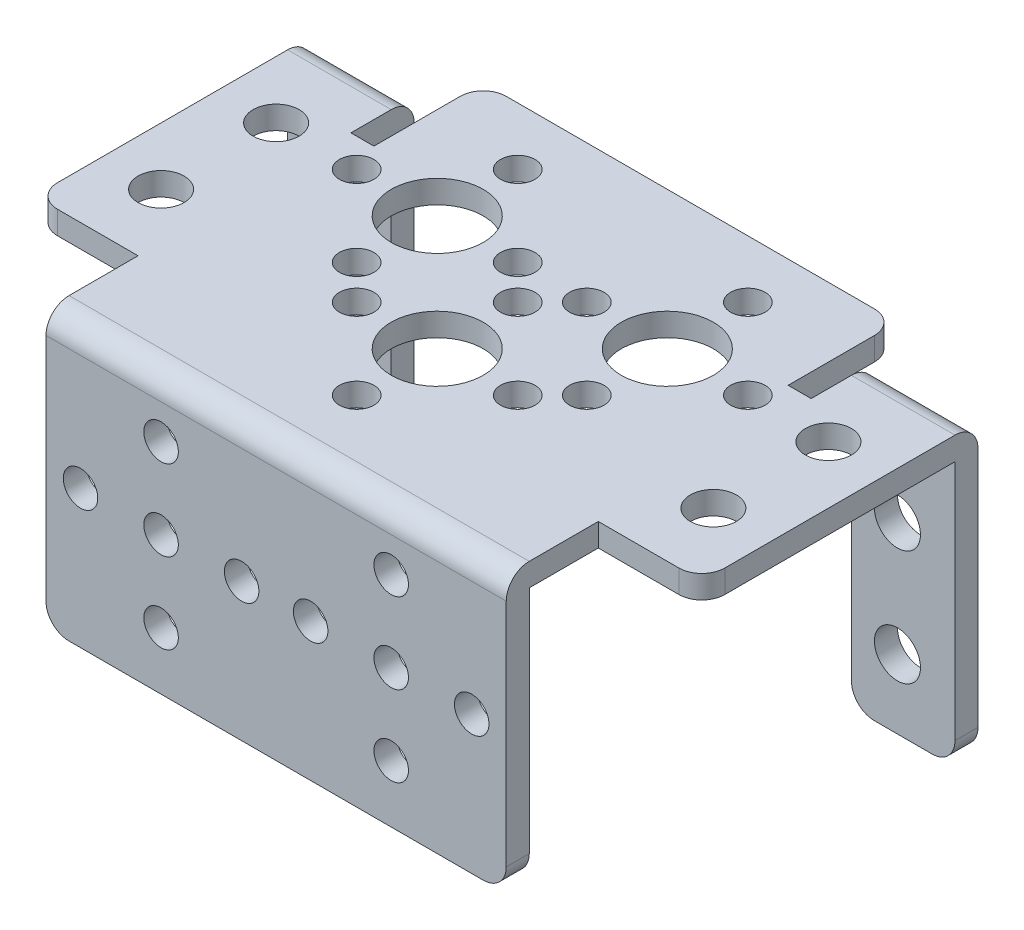
SolidWorks part; units mm, degrees
ref_plane "前视基准面" through (0, 0, 0) normal (0, 0, 1) x (1, 0, 0)
ref_plane "上视基准面" through (0, 0, 0) normal (0, 1, 0) x (1, 0, 0)
ref_plane "右视基准面" through (0, 0, 0) normal (1, 0, 0) x (0, 0, -1)
sketch "底面" plane through (0, 0, 0) normal (0, 1, 0) x (1, 0, 0)
  line L0 (0, 39.6987) -> (0, 22.5) construction
  line L1 (-41.0234, 0) -> (117.127, 0) construction
  line L3 (0, 36) -> (18, 36)
  line L4 (18, 36) -> (18, 26.5)
  line L5 (18, 26.5) -> (20, 26.5)
  line L6 (20, 26.5) -> (20, 32)
  line L7 (20, 32) -> (29, 32)
  line L8 (29, 32) -> (29, 8)
  line L9 (29, 8) -> (20, 8)
  line L10 (20, 8) -> (20, 0)
  line L11 (20, 0) -> (0, 0)
  line L12 (10, 40.3159) -> (10, 15.2594) construction
  line L13 (-9.3197, 14) -> (11.0834, 14) construction
  line L14 (0, 36) -> (0, 22.5)
  line L15 (0, 19.5) -> (0, 18)
  line L16 (0, 19.5) -> (0, 18) construction
  line L17 (0, 10) -> (0, 8.5)
  line L18 (0, 10) -> (0, 8.5) construction
  line L19 (0, 5.5) -> (0, 0)
  line L20 (0, 5.5) -> (0, -49.3691) construction
  line L21 (24, 29.0725) -> (24, 10.3645) construction
  arc A0 (0, 10) -> (0, 18) centre (0, 14) ccw
  arc A1 (0, 5.5) -> (0, 8.5) centre (0, 7) ccw
  arc A2 (0, 19.5) -> (0, 22.5) centre (0, 21) ccw
  circle A3 centre (10, 24) radius 4
  circle A4 centre (10, 31) radius 1.5
  circle A6 centre (17, 24) radius 1.5
  circle A7 centre (10, 17) radius 1.5
  circle A8 centre (3, 24) radius 1.5
  circle A9 centre (7, 14) radius 1.5
  circle A10 centre (24, 24) radius 2
  circle A11 centre (24, 14) radius 2
  point P36 (10, 24)
  dimension "D8" = 8
  dimension "D9" = 3
  dimension "D11" = 3
  dimension "D15" = 8
  dimension "D17" = 3
  dimension "D19" = 4
  dimension "D20" = 3
  dimension "D23" = 4
  dimension "D24" = 4
  dimension "D1" = 36
  dimension "D2" = 18
  dimension "D3" = 9.5
  dimension "D4" = 32
  dimension "D5" = 29
  dimension "D6" = 2
  dimension "D7" = 8
  dimension "D10" = 14
  dimension "D12" = 7
  dimension "D13" = 14
  dimension "D14" = 12
  dimension "D16" = 8
  dimension "D18" = 7
  dimension "D21" = 7
  dimension "D22" = 5
  dimension "D25" = 6
  dimension "D26" = 10
extrude "凸台-拉伸1" add sketch "底面" along normal blind 2
sketch "草图3" plane through (0, 0, -32) normal (0, 0, -1) x (-1, 0, 0)
  line L0 (-20, 0) -> (-20, -23)
  line L1 (-20, -23) -> (-29, -23)
  line L2 (-29, -23) -> (-29, 0)
  line L3 (-29, 0) -> (-20, 0) construction
  line L4 (-29, 2) -> (-29, 0) construction
  line L6 (-24, -21.137) -> (-24, -5.8697) construction
  line L7 (-20, 0) -> (-20, 2)
  line L8 (-20, 2) -> (-29, 2)
  line L9 (-29, 2) -> (-29, 0)
  circle A0 centre (-24, -17) radius 2
  circle A1 centre (-24, -7) radius 2
  dimension "D2" = 4
  dimension "D5" = 4
  dimension "D1" = 23
  dimension "D3" = 6
  dimension "D4" = 5
  dimension "D6" = 10
extrude "凸台-拉伸2" add sketch "草图3" against normal blind 2
sketch "草图4" plane through (0, 0, 0) normal (0, 0, 1) x (1, 0, 0)
  line L0 (20, 0) -> (20, -22)
  line L1 (20, -22) -> (0, -22)
  line L2 (0, -22) -> (0, 0)
  line L3 (0, 0) -> (20, 0)
  line L4 (5.1818, -10) -> (21.285, -10) construction
  circle A0 centre (10, -10) radius 1.5
  circle A1 centre (17, -10) radius 1.5
  circle A2 centre (10, -17) radius 1.5
  circle A3 centre (3, -10) radius 1.5
  circle A4 centre (10, -3) radius 1.5
  point P21 (10, -10)
  dimension "D1" = 3
  dimension "D4" = 3
  dimension "D2" = 10
  dimension "D3" = 7
  dimension "D5" = 22
  dimension "D6" = 12
  dimension "D7" = 4
extrude "凸台-拉伸3" add sketch "草图4" against normal blind 2
fillet "圆角1" radius 2 7 edges at (20, -22, -1) (10, 2, 0) (29, 1, -8) (20, -23, -31) (29, -23, -31) (24.5, 2, -32) (18, 1, -36)
mirror "镜向1" about plane through (0, 0, 0) normal (1, 0, 0) of "凸台-拉伸1", "凸台-拉伸2", "凸台-拉伸3", "圆角1"
